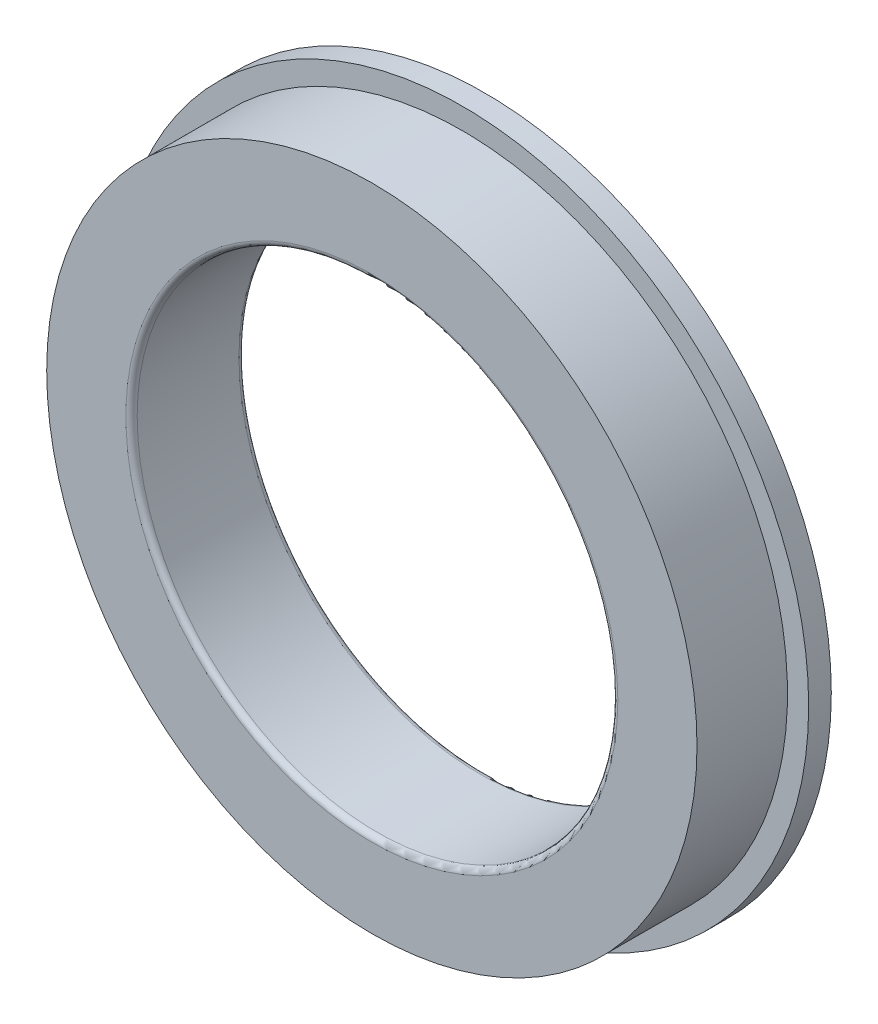
SolidWorks part; units mm, degrees
ref_plane "正面" through (0, 0, 0) normal (0, 0, 1) x (1, 0, 0)
ref_plane "平面" through (0, 0, 0) normal (0, 1, 0) x (1, 0, 0)
ref_plane "右側面" through (0, 0, 0) normal (1, 0, 0) x (0, 0, -1)
sketch "ｽｹｯﾁ1" plane through (0, 0, 0) normal (0, 0, 1) x (1, 0, 0)
  circle A0 centre (0, 0) radius 8.5
  dimension "D1" = 17
extrude "押し出し-薄板1" add sketch "ｽｹｯﾁ1" along normal blind 4 thin
sketch "ｽｹｯﾁ2" plane through (0, 0, 0) normal (0, 0, -1) x (-1, 0, 0)
  circle A0 centre (0, 0) radius 12.25
  dimension "D1" = 24.5
extrude "押し出し-薄板2" add sketch "ｽｹｯﾁ2" against normal blind 0.8 thin thin type one direction reverse wall 0.75
fillet "ﾌｨﾚｯﾄ1" radius 0.2 2 edges at (8.5, 0, 4) (8.5, 0, 0)
